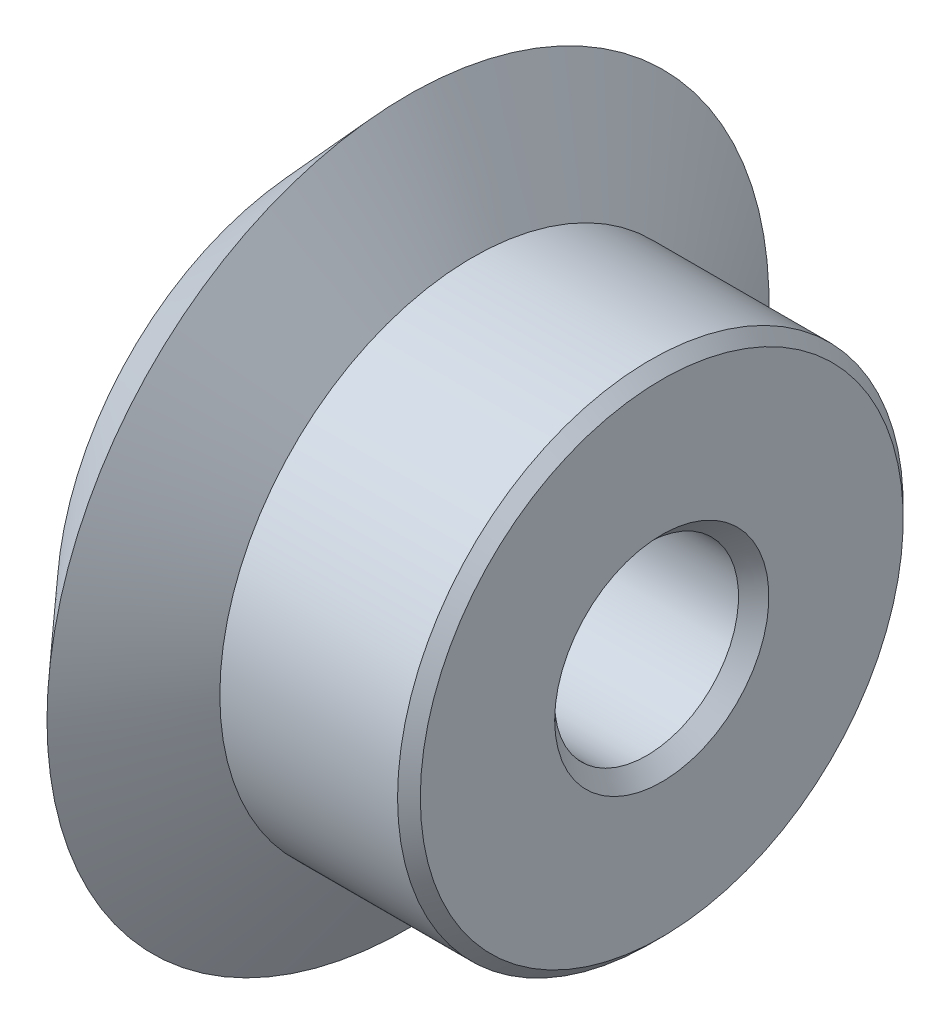
SolidWorks part; units mm, degrees
ref_plane "前视基准面" through (0, 0, 0) normal (0, 0, 1) x (1, 0, 0)
ref_plane "上视基准面" through (0, 0, 0) normal (0, 1, 0) x (1, 0, 0)
ref_plane "右视基准面" through (0, 0, 0) normal (1, 0, 0) x (0, 0, -1)
sketch "草图1" plane through (0, 0, 0) normal (0, 0, 1) x (1, 0, 0)
  line L0 (-21, 0) -> (-21, 14.8)
  line L1 (-21, 14.8) -> (-22.83, 16.6694)
  line L2 (-22.83, 16.6694) -> (-16.56, 23.56)
  line L3 (-16.56, 23.56) -> (-12.34, 16.5)
  line L4 (-12.34, 16.5) -> (-0.7425, 16.5)
  line L5 (-0.7425, 16.5) -> (0, 15.7575)
  line L6 (0, 15.7575) -> (0, 0)
  line L7 (0, 0) -> (-21, 0)
  line L8 (0, 0) -> (-21, 0) construction
revolve "旋转1" add sketch "草图1" angle 360 about L8
sketch "草图2" plane through (0, 0, 0) normal (0, 0, 1) x (1, 0, 0)
  line L0 (-21, 0) -> (-21, 6.99)
  line L1 (-21, 6.99) -> (-20.01, 6)
  line L2 (-20.01, 6) -> (-0.99, 6)
  line L3 (-0.99, 6) -> (0, 6.99)
  line L4 (0, 6.99) -> (0, 0)
  line L5 (0, 0) -> (-21, 0)
  line L6 (0, 0) -> (-21, 0) construction
revolve "切除-旋转1" cut sketch "草图2" angle 360 about L6
ref_plane "基准面4" through (-6, 0, 0) normal (1, 0, 0) x (0, 0, -1)
